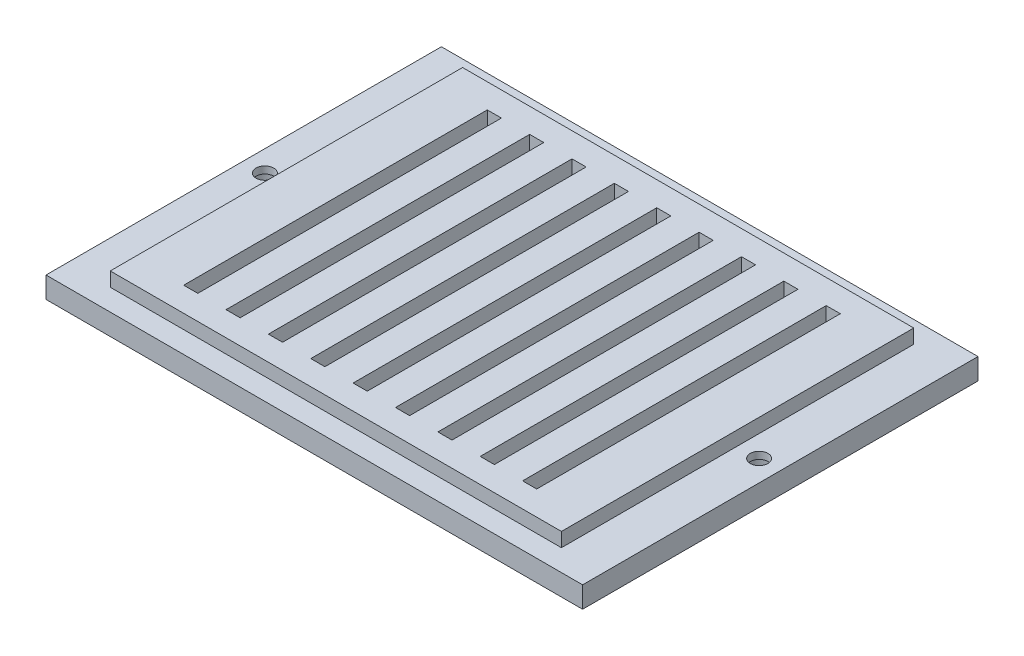
SolidWorks part; units mm, degrees
ref_plane "Front Plane" through (0, 0, 0) normal (0, 0, 1) x (1, 0, 0)
ref_plane "Top Plane" through (0, 0, 0) normal (0, 1, 0) x (1, 0, 0)
ref_plane "Right Plane" through (0, 0, 0) normal (1, 0, 0) x (0, 0, -1)
sketch "Sketch1" plane through (0, 0, 0) normal (0, 1, 0) x (1, 0, 0)
  line L1 (-38, -28) -> (38, -28)
  line L2 (-38, -28) -> (-38, 28)
  line L3 (-38, 28) -> (38, 28)
  line L4 (38, -28) -> (38, 28)
  line L5 (-38, -28) -> (38, 28) construction
  line L6 (-38, 28) -> (38, -28) construction
  point P0 (0, 0)
  dimension "D1" = 76
  dimension "D2" = 56
extrude "Boss-Extrude1" add sketch "Sketch1" along normal blind 3
sketch "Sketch2" plane through (0, 3, 0) normal (0, 1, 0) x (1, 0, 0)
  line L1 (-31.95, -24.95) -> (31.95, -24.95)
  line L2 (-31.95, -24.95) -> (-31.95, 24.95)
  line L3 (-31.95, 24.95) -> (31.95, 24.95)
  line L4 (31.95, -24.95) -> (31.95, 24.95)
  line L5 (-31.95, -24.95) -> (31.95, 24.95) construction
  line L6 (-31.95, 24.95) -> (31.95, -24.95) construction
  point P0 (0, 0)
  point P5 (0, 0)
  dimension "D1" = 49.9
  dimension "D2" = 63.9
extrude "Boss-Extrude2" add sketch "Sketch2" along normal blind 2 from surface at 0 starting at face at (0, 3, 0)
sketch "Sketch3" plane through (0, 0, 0) normal (0, -1, 0) x (1, 0, 0)
  line L0 (0, 0) -> (0, 45.9117) construction
  line L1 (-38, -28) -> (-38, 28) construction
  circle A0 centre (-35, 0) radius 2.25
  circle A1 centre (35, 0) radius 2.25
  dimension "D2" = 4.5
  dimension "D1" = 3
extrude "Cut-Extrude1" cut sketch "Sketch3" against normal blind 2
sketch "Sketch4" plane through (0, 0, 0) normal (0, -1, 0) x (1, 0, 0)
  line L0 (0, 0) -> (0, 17.5189) construction
  circle A0 centre (-35, 0) radius 1.25
  circle A1 centre (35, 0) radius 1.25
  dimension "D1" = 2.5
extrude "Cut-Extrude2" cut sketch "Sketch4" against normal up to next
sketch "Sketch5" plane through (0, 0, 0) normal (0, -1, 0) x (1, 0, 0)
  line L0 (5, -21.5) -> (5, 21.5)
  line L1 (-1, -21.5) -> (1, -21.5)
  line L2 (-1, -21.5) -> (-1, 21.5)
  line L3 (-1, 21.5) -> (1, 21.5)
  line L4 (1, -21.5) -> (1, 21.5)
  line L5 (-1, -21.5) -> (1, 21.5) construction
  line L6 (-1, 21.5) -> (1, -21.5) construction
  line L7 (5, -21.5) -> (7, -21.5)
  line L8 (7, -21.5) -> (7, 21.5)
  line L9 (5, 21.5) -> (7, 21.5)
  line L10 (11, -21.5) -> (11, 21.5)
  line L11 (11, -21.5) -> (13, -21.5)
  line L12 (13, -21.5) -> (13, 21.5)
  line L13 (11, 21.5) -> (13, 21.5)
  line L14 (17, -21.5) -> (17, 21.5)
  line L15 (17, -21.5) -> (19, -21.5)
  line L16 (19, -21.5) -> (19, 21.5)
  line L17 (17, 21.5) -> (19, 21.5)
  line L18 (23, -21.5) -> (23, 21.5)
  line L19 (23, -21.5) -> (25, -21.5)
  line L20 (25, -21.5) -> (25, 21.5)
  line L21 (23, 21.5) -> (25, 21.5)
  line L22 (-7, -21.5) -> (-7, 21.5)
  line L23 (-7, -21.5) -> (-5, -21.5)
  line L24 (-5, -21.5) -> (-5, 21.5)
  line L25 (-7, 21.5) -> (-5, 21.5)
  line L26 (-13, -21.5) -> (-13, 21.5)
  line L27 (-13, -21.5) -> (-11, -21.5)
  line L28 (-11, -21.5) -> (-11, 21.5)
  line L29 (-13, 21.5) -> (-11, 21.5)
  line L30 (-19, -21.5) -> (-19, 21.5)
  line L31 (-19, -21.5) -> (-17, -21.5)
  line L32 (-17, -21.5) -> (-17, 21.5)
  line L33 (-19, 21.5) -> (-17, 21.5)
  line L34 (-25, -21.5) -> (-25, 21.5)
  line L35 (-25, -21.5) -> (-23, -21.5)
  line L36 (-23, -21.5) -> (-23, 21.5)
  line L37 (-25, 21.5) -> (-23, 21.5)
  point P0 (0, 0)
  dimension "D1" = 2
  dimension "D2" = 43
  dimension "D3" = 5
  dimension "D4" = 5
extrude "Cut-Extrude3" cut sketch "Sketch5" against normal through all
